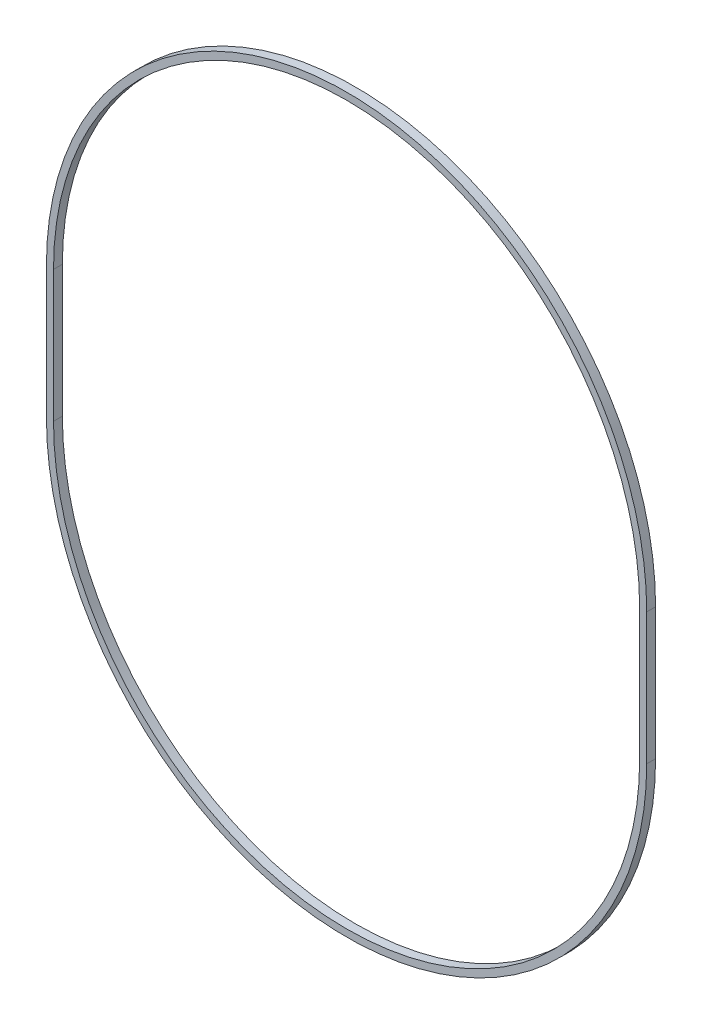
SolidWorks part; units mm, degrees
ref_plane "Front Plane" through (0, 0, 0) normal (0, 0, 1) x (1, 0, 0)
ref_plane "Top Plane" through (0, 0, 0) normal (0, 1, 0) x (1, 0, 0)
ref_plane "Right Plane" through (0, 0, 0) normal (1, 0, 0) x (0, 0, -1)
sketch "Sketch1" plane through (0, 0, 0) normal (0, 0, 1) x (1, 0, 0)
  line B0 (-127.19, 27.875) -> (-127.19, -27.875)
  line B1 (-98, 27.875) -> (-98, -27.875)
  line B2 (98, -27.875) -> (98, 27.875)
  line B3 (-127.19, 27.875) -> (-127.19, -27.875)
  line B4 (127.19, -27.875) -> (127.19, 27.875)
  line B5 (124.19, -27.875) -> (124.19, 27.875)
  line B6 (-124.19, 27.875) -> (-124.19, -27.875)
  line B7 (95, -27.875) -> (95, 27.875)
  line B8 (-95, 27.875) -> (-95, -27.875)
  arc B9 (-98, -27.875) -> (98, -27.875) centre (0, -27.875) ccw
  arc B10 (98, 27.875) -> (-98, 27.875) centre (0, 27.875) ccw
  arc B11 (127.19, 27.875) -> (-127.19, 27.875) centre (0, 27.875) ccw
  arc B12 (-127.19, -27.875) -> (127.19, -27.875) centre (0, -27.875) ccw
  arc B13 (124.19, 27.875) -> (-124.19, 27.875) centre (0, 27.875) ccw
  arc B14 (-124.19, -27.875) -> (124.19, -27.875) centre (0, -27.875) ccw
  arc B15 (127.19, 27.875) -> (-127.19, 27.875) centre (0, 27.875) ccw
  arc B16 (124.19, 27.875) -> (-124.19, 27.875) centre (0, 27.875) ccw
  arc B17 (95, 27.875) -> (-95, 27.875) centre (0, 27.875) ccw
  arc B18 (95, 27.875) -> (-95, 27.875) centre (0, 27.875) ccw
  arc B19 (-95, -27.875) -> (95, -27.875) centre (0, -27.875) ccw
sketch_block_instance "Gasket Rims-1"
sketch_block "Gasket Rims"
extrude "Boss-Extrude1" add sketch "Sketch1" along normal mid plane 3.75 contours B0 B12 B4 B11 B14 B6 B13 B5
